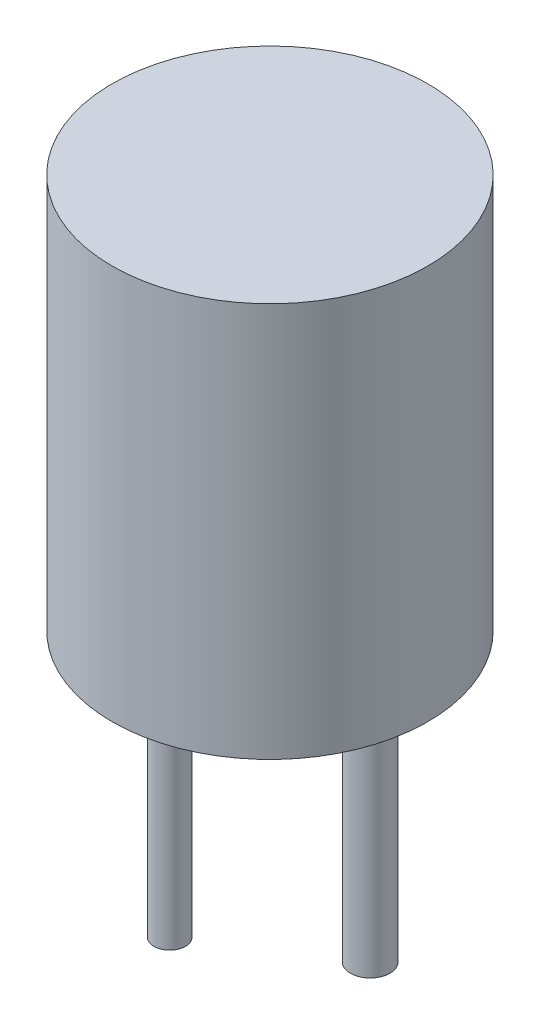
SolidWorks part; units mm, degrees
ref_plane "前视基准面" through (0, 0, 0) normal (0, 0, 1) x (1, 0, 0)
ref_plane "上视基准面" through (0, 0, 0) normal (0, 1, 0) x (1, 0, 0)
ref_plane "右视基准面" through (0, 0, 0) normal (1, 0, 0) x (0, 0, -1)
sketch "草图1" plane through (0, 0, 0) normal (0, 1, 0) x (1, 0, 0)
  circle A0 centre (0, 0) radius 4
  dimension "D1" = 8
extrude "拉伸1" add sketch "草图1" along normal blind 10
sketch "草图2" plane through (0, 0, 0) normal (0, -1, 0) x (1, 0, 0)
  line L0 (4.8023, 0) -> (-11.2367, 0) construction
  circle A0 centre (-2.54, 0) radius 0.4
  dimension "D2" = 0.8
  dimension "D1" = 2.54
extrude "拉伸2" add sketch "草图2" along normal blind 8
sketch "草图3" plane through (0, 0, 0) normal (0, -1, 0) x (1, 0, 0)
  line L0 (7.1249, 0) -> (-2.8562, 0) construction
  circle A0 centre (2.54, 0) radius 0.5
  dimension "D1" = 1
  dimension "D2" = 2.54
extrude "拉伸3" add sketch "草图3" along normal blind 6
